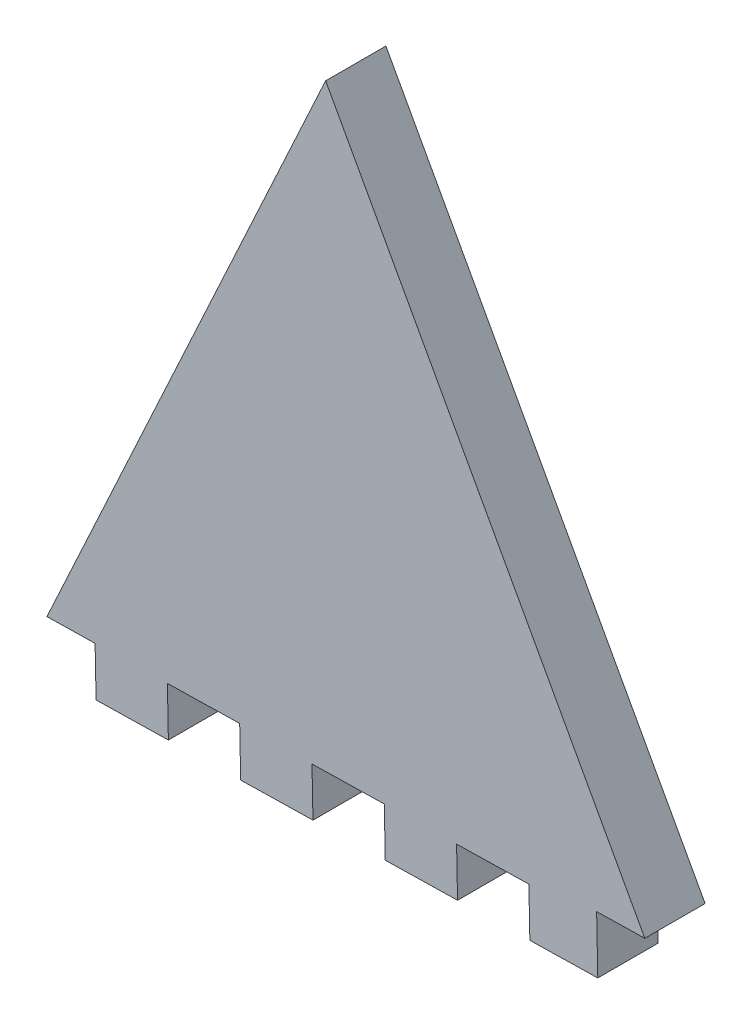
SolidWorks part; units mm, degrees
ref_plane "Front Plane" through (0, 0, 0) normal (0, 0, 1) x (1, 0, 0)
ref_plane "Top Plane" through (0, 0, 0) normal (0, 1, 0) x (1, 0, 0)
ref_plane "Right Plane" through (0, 0, 0) normal (1, 0, 0) x (0, 0, -1)
sketch "Sketch1" plane through (0, 0, 0) normal (0, 0, 1) x (1, 0, 0)
  line L0 (-16.3406, 2.2321) -> (-1.6534, 34.0262)
  line L1 (-16.3406, 2.2321) -> (-13.8011, 2.2832)
  line L2 (-13.8011, 2.2832) -> (-13.7496, -0.2767)
  line L3 (-13.7496, -0.2767) -> (-9.9404, -0.2)
  line L4 (-9.9404, -0.2) -> (-9.9919, 2.3598)
  line L5 (-9.9919, 2.3598) -> (-6.1826, 2.4365)
  line L6 (-6.1826, 2.4365) -> (-6.1311, -0.1234)
  line L7 (-6.1311, -0.1234) -> (-2.3219, -0.0467)
  line L8 (-2.3219, -0.0467) -> (-2.373, 2.4928)
  line L9 (-2.373, 2.4928) -> (1.4362, 2.5694)
  line L10 (1.4873, 0.0299) -> (1.4362, 2.5694)
  line L11 (5.2966, 0.1066) -> (1.4873, 0.0299)
  line L12 (5.2455, 2.6461) -> (5.2966, 0.1066)
  line L13 (9.0547, 2.7227) -> (5.2455, 2.6461)
  line L14 (9.1058, 0.1832) -> (9.0547, 2.7227)
  line L15 (12.6857, 0.2553) -> (9.1058, 0.1832)
  line L16 (12.6253, 3.2549) -> (12.6857, 0.2553)
  line L17 (15.1648, 3.306) -> (12.6253, 3.2549)
  line L18 (-1.6534, 34.0262) -> (15.1648, 3.306)
extrude "Boss-Extrude1" add sketch "Sketch1" along normal blind 3.175
